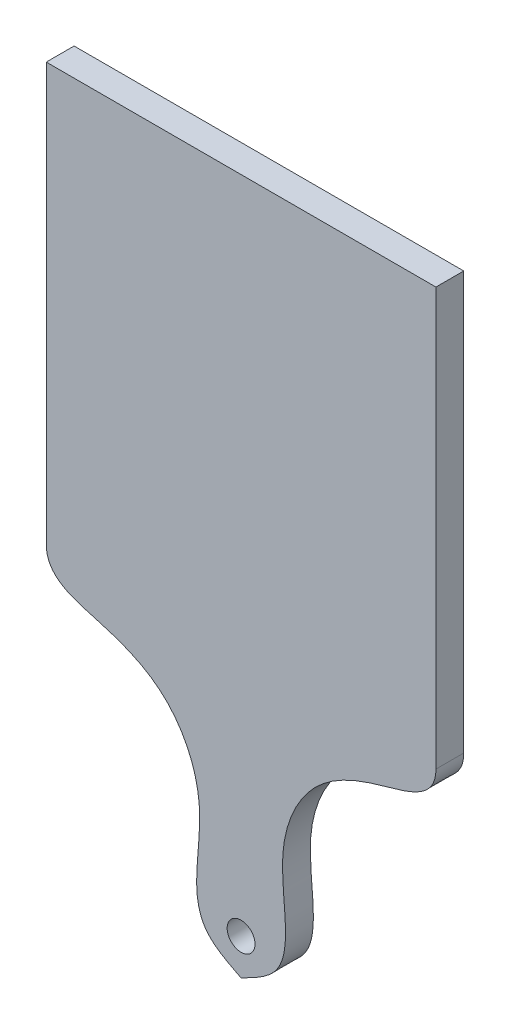
SolidWorks part; units mm, degrees
ref_plane "Płaszczyzna przednia" through (0, 0, 0) normal (0, 0, 1) x (1, 0, 0)
ref_plane "Płaszczyzna górna" through (0, 0, 0) normal (0, 1, 0) x (1, 0, 0)
ref_plane "Płaszczyzna prawa" through (0, 0, 0) normal (1, 0, 0) x (0, 0, -1)
sketch "Sketch1" plane through (0, 0, 0) normal (0, 0, 1) x (1, 0, 0)
  line L0 (0, 1678.9374) -> (0, -94.9115) construction
  line L1 (70, 87) -> (70, 237)
  line L2 (70, 237) -> (-70, 237)
  line L3 (-70, 87) -> (-70, 237)
  spline S0 degree 3 poles (0, -13) (4.6059, -10.654) (21.3855, -2.1074) (9.9082, 31.1915) (24.2407, 61.8897) (47.8576, 72.5708) (70, 76.6477) (70, 87) knots 0 0 0 0 0.050957 0.185636 0.29003 0.381689 0.470019 0.470019 0.470019 0.470019
  spline S1 degree 3 poles (0, -13) (-4.6059, -10.654) (-21.3855, -2.1074) (-9.9082, 31.1915) (-24.2407, 61.8897) (-47.8576, 72.5708) (-70, 76.6477) (-70, 87) knots 0 0 0 0 0.050957 0.185636 0.29003 0.381689 0.470019 0.470019 0.470019 0.470019
  point P11 (0, 237)
  dimension "D1" = 13
  dimension "D2" = 8
  dimension "D3" = 24
  dimension "D4" = 46
  dimension "D5" = 30
  dimension "D6" = 54
  dimension "D7" = 73
  dimension "D8" = 85
  dimension "D9" = 100
  dimension "D10" = 100
  dimension "D11" = 250
  dimension "D12" = 140
extrude "Boss-Extrude1" add sketch "Sketch1" along normal blind 10
sketch "Sketch2" plane through (0, 0, 0) normal (0, 0, -1) x (-1, 0, 0)
  circle A0 centre (0, 0) radius 5
  dimension "D1" = 10
extrude "Cut-Extrude1" cut sketch "Sketch2" against normal blind 10
